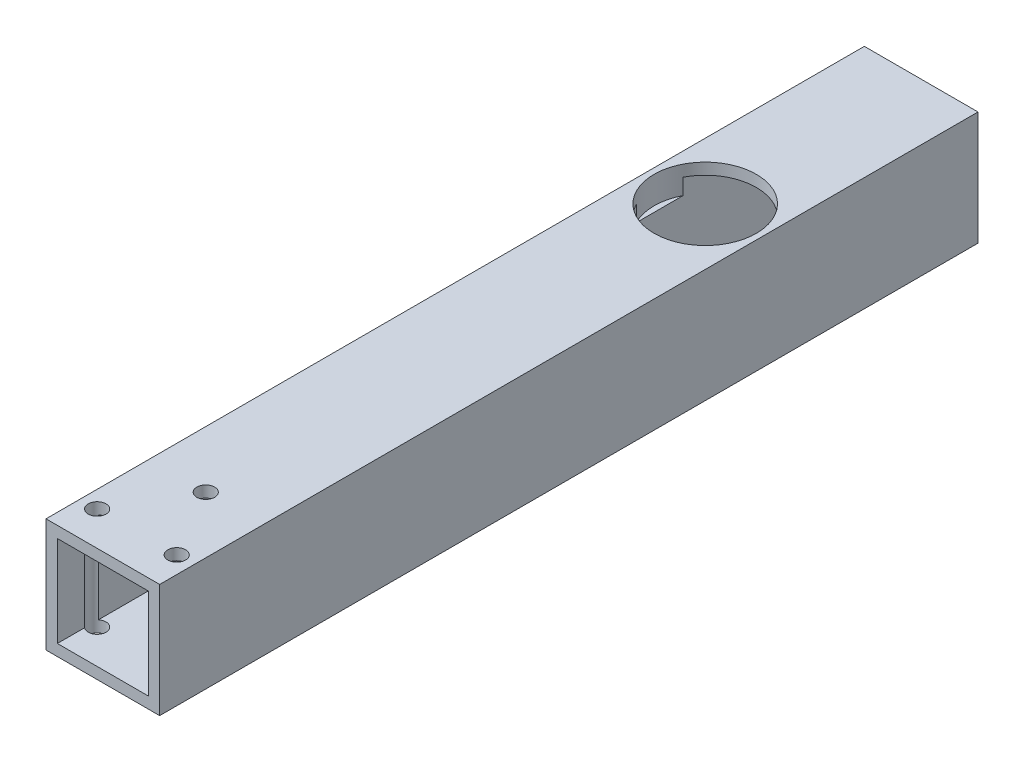
SolidWorks part; units mm, degrees
ref_plane "Front Plane" through (0, 0, 0) normal (0, 0, 1) x (1, 0, 0)
ref_plane "Top Plane" through (0, 0, 0) normal (0, 1, 0) x (1, 0, 0)
ref_plane "Right Plane" through (0, 0, 0) normal (1, 0, 0) x (0, 0, -1)
sketch "Sketch1" plane through (0, 0, 0) normal (0, 0, 1) x (1, 0, 0)
  line L0 (-12.7, 12.7) -> (12.7, 12.7)
  line L2 (-15.875, 15.875) -> (15.875, 15.875)
  line L3 (-15.875, 15.875) -> (-15.875, -15.875)
  line L4 (-15.875, -15.875) -> (15.875, -15.875)
  line L5 (15.875, 15.875) -> (15.875, -15.875)
  line L10 (12.7, 12.7) -> (12.7, -12.7)
  line L11 (-12.7, -12.7) -> (12.7, -12.7)
  line L12 (-12.7, 12.7) -> (-12.7, -12.7)
  point P12 (0, 15.875)
  point P14 (15.875, 0)
  dimension "Wall Thickness" = 3.175
  dimension "Outside Width" = 31.75
  dimension "Outside Height" = 31.75
  dimension "Inside Height" = 25.4
  dimension "Inside Width" = 25.4
sketch "Sketch2" plane through (0, 0, 0) normal (1, 0, 0) x (0, 0, -1)
  line L0 (114.3, 0) -> (-114.3, 0)
  point P4 (0, 0)
  point P7 (-114.3, 0)
  point P10 (114.3, 0)
  dimension "Length" = 228.6
sketch "Sketch3" plane through (0, 0, 0) normal (0, 0, 1) x (1, 0, 0)
  line L21 (15.875, 15.875) -> (-15.875, 15.875)
  line L22 (15.875, -15.875) -> (15.875, 15.875)
  line L23 (-15.875, -15.875) -> (15.875, -15.875)
  line L24 (-15.875, 15.875) -> (-15.875, -15.875)
  line L25 (15.875, 15.875) -> (-15.875, 15.875)
  line L26 (15.875, -15.875) -> (15.875, 15.875)
  line L27 (-15.875, -15.875) -> (15.875, -15.875)
  line L28 (-15.875, 15.875) -> (-15.875, -15.875)
  line L29 (12.7, 12.7) -> (-12.7, 12.7)
  line L30 (12.7, -12.7) -> (12.7, 12.7)
  line L31 (-12.7, -12.7) -> (12.7, -12.7)
  line L32 (-12.7, 12.7) -> (-12.7, -12.7)
  line L33 (12.7, 12.7) -> (-12.7, 12.7)
  line L34 (12.7, -12.7) -> (12.7, 12.7)
  line L35 (-12.7, -12.7) -> (12.7, -12.7)
  line L36 (-12.7, 12.7) -> (-12.7, -12.7)
  dimension "D1" = 0
  dimension "D2" = 0
extrude "Boss-Extrude1" add sketch "Sketch3" along normal up to vertex (114.3 mm away) and the other way up to vertex (114.3 mm away) up to point (0, 0, 114.3) other way up to point (0, 0, -114.3)
sketch "Drawing Reference" plane through (0, 0, 0) normal (1, 0, 0) x (0, 0, -1)
  line L0 (-114.3, 0) -> (114.3, 0) construction
  line L1 (0, -15.875) -> (0, 15.875) construction
  line L2 (-114.3, -15.875) -> (114.3, -15.875) construction
  line L5 (-114.3, 15.875) -> (114.3, 15.875) construction
  point P7 (-91.44, 0)
  point P8 (91.44, 0)
  dimension "D1" = 22.86
sketch "Sketch4" plane through (0, 15.875, 0) normal (0, 1, 0) x (1, 0, 0)
  line L0 (0, -114.3) -> (0, -104.775) construction
  line L1 (15.875, -114.3) -> (-15.875, -114.3) construction
  line L2 (0, -104.775) -> (11.1125, -104.775) construction
  line L3 (0, -104.775) -> (-11.1125, -104.775) construction
  line L4 (0, -104.775) -> (0, 53.975) construction
  line L5 (0, -104.775) -> (0, -98.2472) construction
  dimension "D1" = 158.75
  dimension "D2" = 22.225
  dimension "D3" = 9.525
hole_wizard "#10 Clearance Hole1" positions "Sketch5" profile "Sketch6" hole size "#10" standard "ANSI Inch" end condition through all
sketch "Sketch5" plane through (0, 15.875, 0) normal (0, 1, 0) x (1, 0, 0)
  point P0 (-11.1125, -104.775)
  point P3 (11.1125, -104.775)
  point P7 (0, -85.5472)
sketch "Sketch6" plane through (-11.1125, 15.875, 104.775) normal (1, 0, 0) x (0, 0, 1)
  line L0 (0, 0) -> (0, 31.75)
  line L1 (0, 31.75) -> (2.4892, 31.75)
  line L2 (2.4892, 31.75) -> (2.4892, 0)
  line L5 (2.4892, 0) -> (0, 0)
  line L11 (0, -6.35) -> (0, 107.95) construction
  dimension "Thru Hole Dia." = 4.9784
  dimension "Thru Hole Depth" = 31.75
sketch "Sketch7" plane through (0, 15.875, 0) normal (0, 1, 0) x (1, 0, 0)
  circle A0 centre (0, 53.975) radius 14.2875
  dimension "D1" = 28.575
extrude "Cut-Extrude1" cut sketch "Sketch7" against normal blind 7.62
sketch "Sketch8" plane through (0, -15.875, 0) normal (0, -1, 0) x (1, 0, 0)
  circle A0 centre (0, -53.975) radius 14.2875
  dimension "D1" = 28.575
extrude "Cut-Extrude2" cut sketch "Sketch8" against normal blind 7.62
equation "\"D1@Drawing Reference\"=\"Outside Width@Sketch1\" * 0.72"
